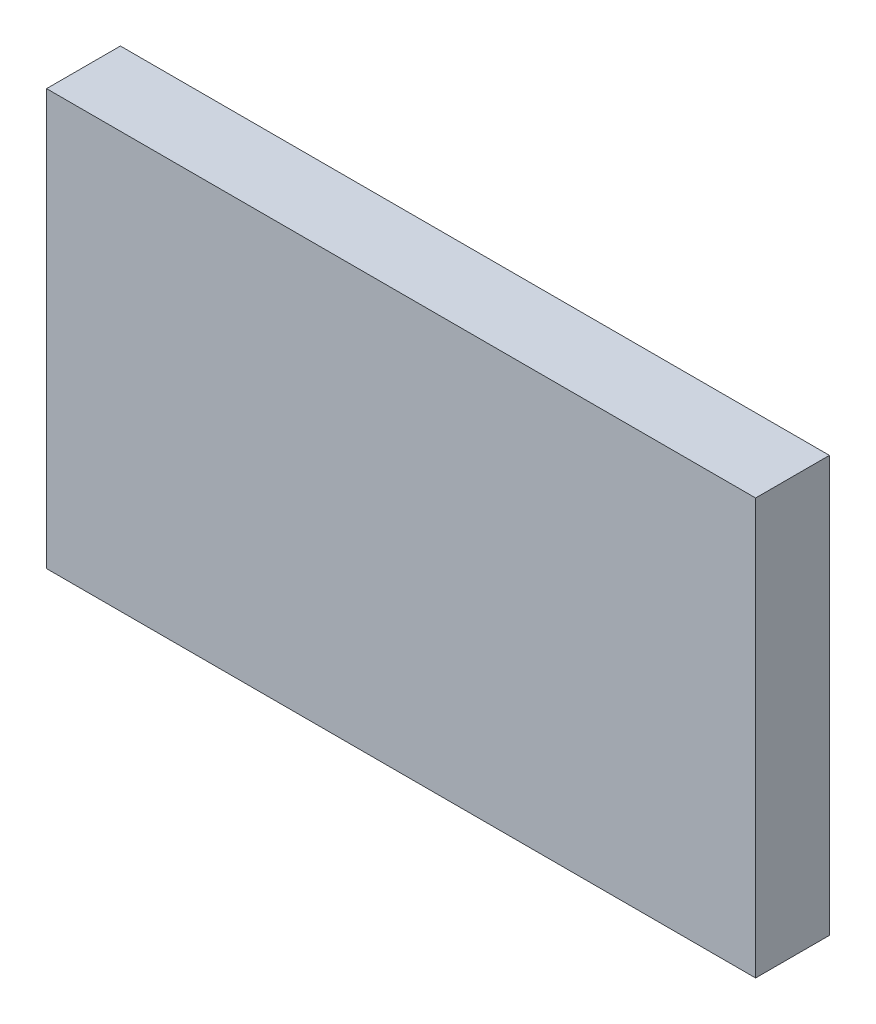
SolidWorks part; units mm, degrees
ref_plane "Plano frontal" through (0, 0, 0) normal (0, 0, 1) x (1, 0, 0)
ref_plane "Plano superior" through (0, 0, 0) normal (0, 1, 0) x (1, 0, 0)
ref_plane "Plano direito" through (0, 0, 0) normal (1, 0, 0) x (0, 0, -1)
sketch "Esboço1" plane through (0, 0, 0) normal (0, 0, 1) x (1, 0, 0)
  line L0 (-670.5128, 1870.5481) -> (59.4872, 1442.5481) construction
  line L1 (-670.5128, 1870.5481) -> (59.4872, 1870.5481)
  line L2 (-670.5128, 1870.5481) -> (-670.5128, 1442.5481)
  line L3 (-670.5128, 1442.5481) -> (59.4872, 1442.5481)
  line L4 (59.4872, 1870.5481) -> (59.4872, 1442.5481)
extrude "Ressalto-extrusão1" add sketch "Esboço1" along normal blind 76 contours L2 L3 L4 L1
